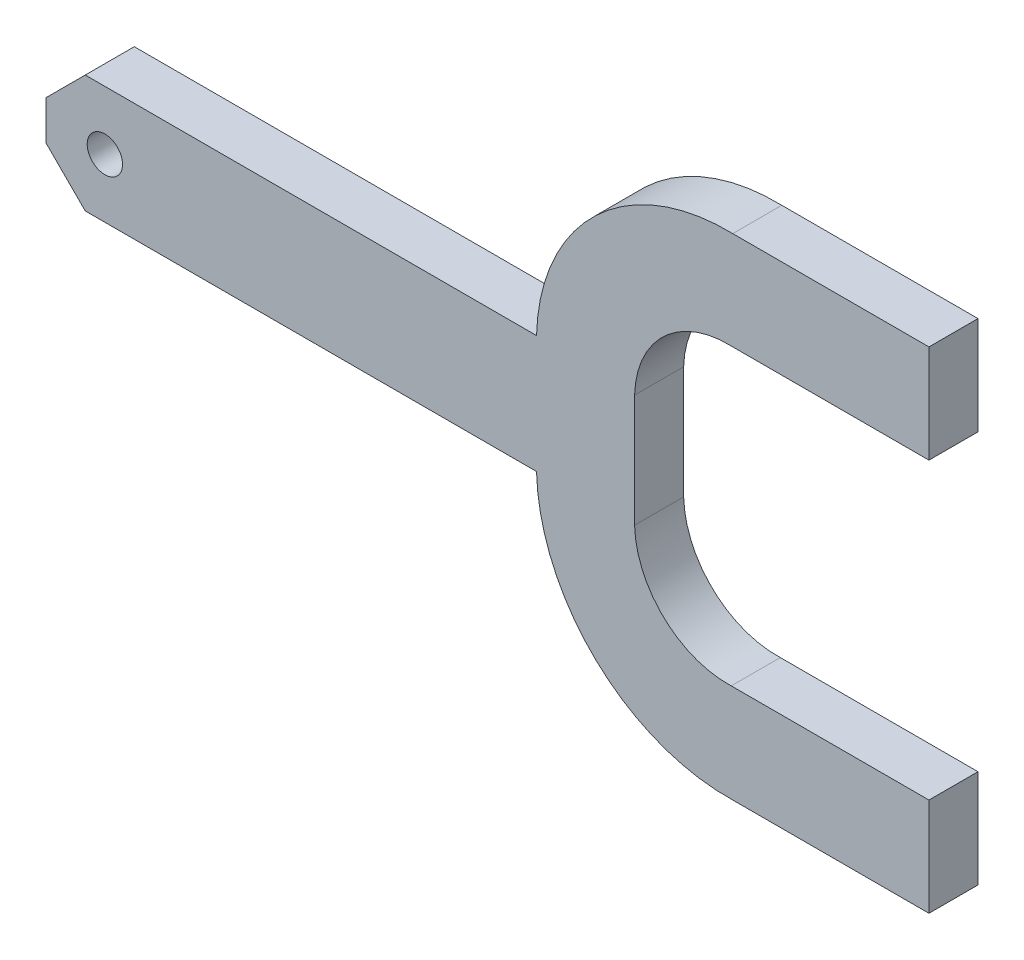
SolidWorks part; units mm, degrees
ref_plane "Front Plane" through (0, 0, 0) normal (0, 0, 1) x (1, 0, 0)
ref_plane "Top Plane" through (0, 0, 0) normal (0, 1, 0) x (1, 0, 0)
ref_plane "Right Plane" through (0, 0, 0) normal (1, 0, 0) x (0, 0, -1)
sketch "Sketch1" plane through (0, 0, 0) normal (0, 0, 1) x (1, 0, 0)
  line L0 (0, 6) -> (128.2333, 6) construction
  line L1 (4, 0) -> (50, 0)
  line L2 (0, 8) -> (0, 4)
  line L3 (50, 12) -> (4, 12)
  line L4 (50, 0) -> (50, 12)
  line L5 (50, 31) -> (90, 31) construction
  line L6 (50, 31) -> (50, -19) construction
  line L7 (50, -19) -> (90, -19) construction
  line L8 (90, 31) -> (90, -19) construction
  line L9 (90, 31) -> (70, 31)
  line L10 (90, -19) -> (70, -19)
  line L11 (90, 21) -> (69.849, 21)
  line L12 (90, -9) -> (69.849, -9)
  line L13 (59.9967, 11.7437) -> (59.9967, 0.2563)
  line L14 (90, 31) -> (90, 21)
  line L15 (90, -9) -> (90, -19)
  line L16 (4, 12) -> (0, 8)
  line L17 (0, 4) -> (4, 0)
  arc A0 (70, 31) -> (50, 12) centre (69.5, 11.5) ccw
  arc A1 (70, -19) -> (50, 0) centre (69.5, 0.5) cw
  arc A2 (69.849, 21) -> (59.9967, 11.7437) centre (69.5, 11.5) ccw
  arc A3 (69.849, -9) -> (59.9967, 0.2563) centre (69.5, 0.5) cw
  circle A6 centre (6, 6) radius 1.8
  point P0 (0, 0)
  point P2 (0, 12)
  point P11 (90, 6)
  point P26 (0, 0)
  point P29 (0, 12)
  dimension "D7" = 4
  dimension "D8" = 3.6
  dimension "D1" = 50
  dimension "D2" = 12
  dimension "D3" = 40
  dimension "D4" = 50
  dimension "D9" = 45
  dimension "D10" = 4
  dimension "D11" = 45
  dimension "D5" = 10
  dimension "D6" = 10
extrude "Boss-Extrude2" add sketch "Sketch1" along normal blind 5
